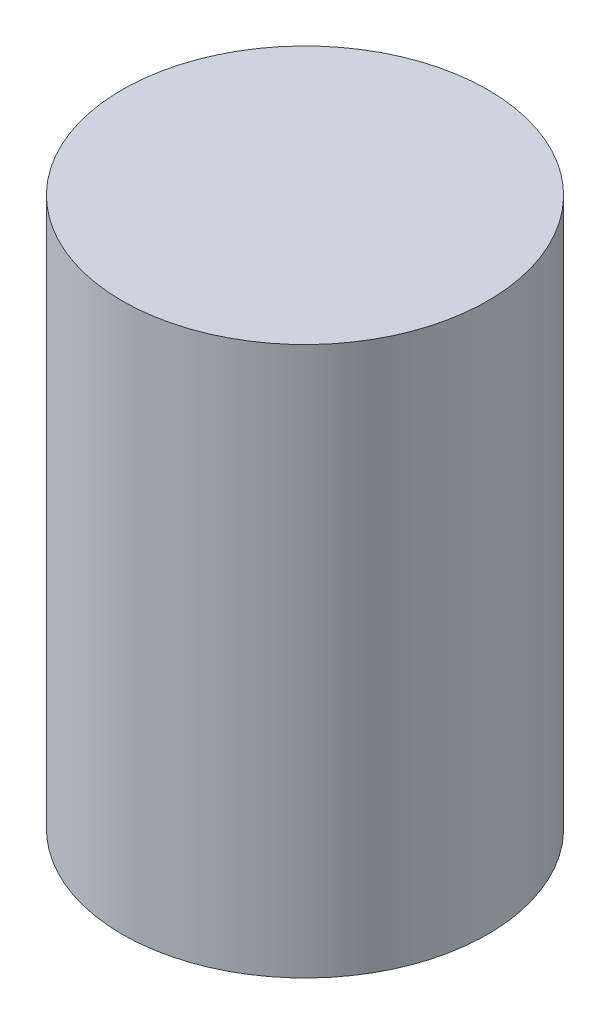
SolidWorks part; units mm, degrees
ref_plane "Front Plane" through (0, 0, 0) normal (0, 0, 1) x (1, 0, 0)
ref_plane "Top Plane" through (0, 0, 0) normal (0, 1, 0) x (1, 0, 0)
ref_plane "Right Plane" through (0, 0, 0) normal (1, 0, 0) x (0, 0, -1)
sketch "Sketch2" plane through (0, 0, 0) normal (0, 1, 0) x (1, 0, 0)
  circle A0 centre (0, 0) radius 10
  dimension "D1" = 20
extrude "Boss-Extrude1" add sketch "Sketch2" along normal blind 30
